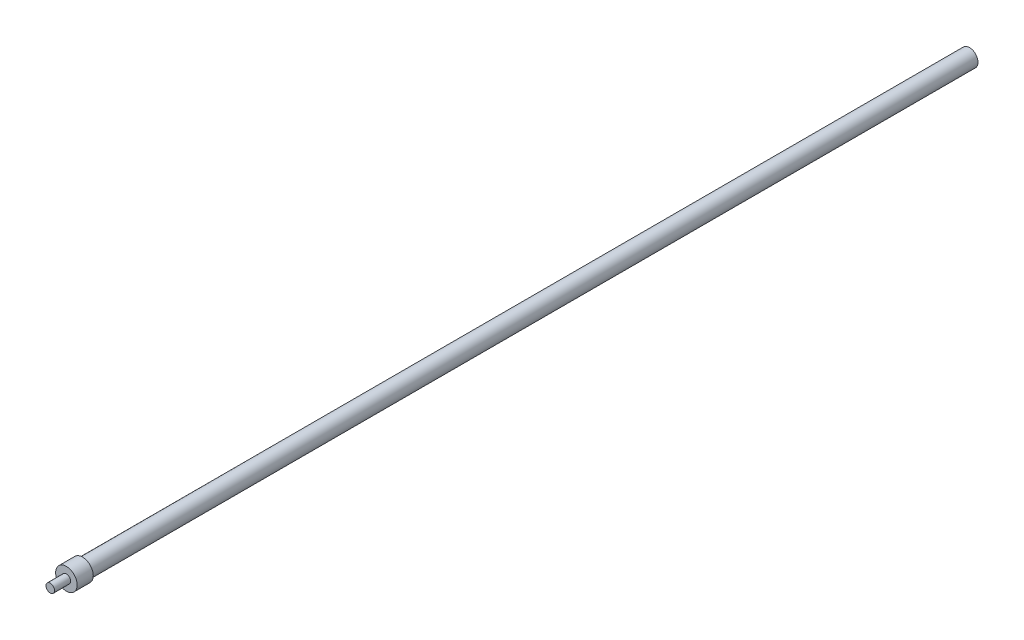
SolidWorks part; units mm, degrees
ref_plane "Alzado" through (0, 0, 0) normal (0, 0, 1) x (1, 0, 0)
ref_plane "Planta" through (0, 0, 0) normal (0, 1, 0) x (1, 0, 0)
ref_plane "Vista lateral" through (0, 0, 0) normal (1, 0, 0) x (0, 0, -1)
sketch "Croquis1" plane through (0, 0, 0) normal (0, 0, 1) x (1, 0, 0)
  circle A0 centre (0, 0) radius 6.35
  dimension "D1" = 12.7
extrude "Saliente-Extruir1" add sketch "Croquis1" along normal blind 660
sketch "Croquis4" plane through (0, 0, 660) normal (0, 0, 1) x (1, 0, 0)
  circle A0 centre (0, 0) radius 8
  dimension "D1" = 16
extrude "Saliente-Extruir2" add sketch "Croquis4" along normal blind 12
sketch "Croquis5" plane through (0, 0, 672) normal (0, 0, 1) x (1, 0, 0)
  circle A0 centre (0, 0) radius 3.175
  dimension "D1" = 6.35
extrude "Saliente-Extruir3" add sketch "Croquis5" along normal blind 12
